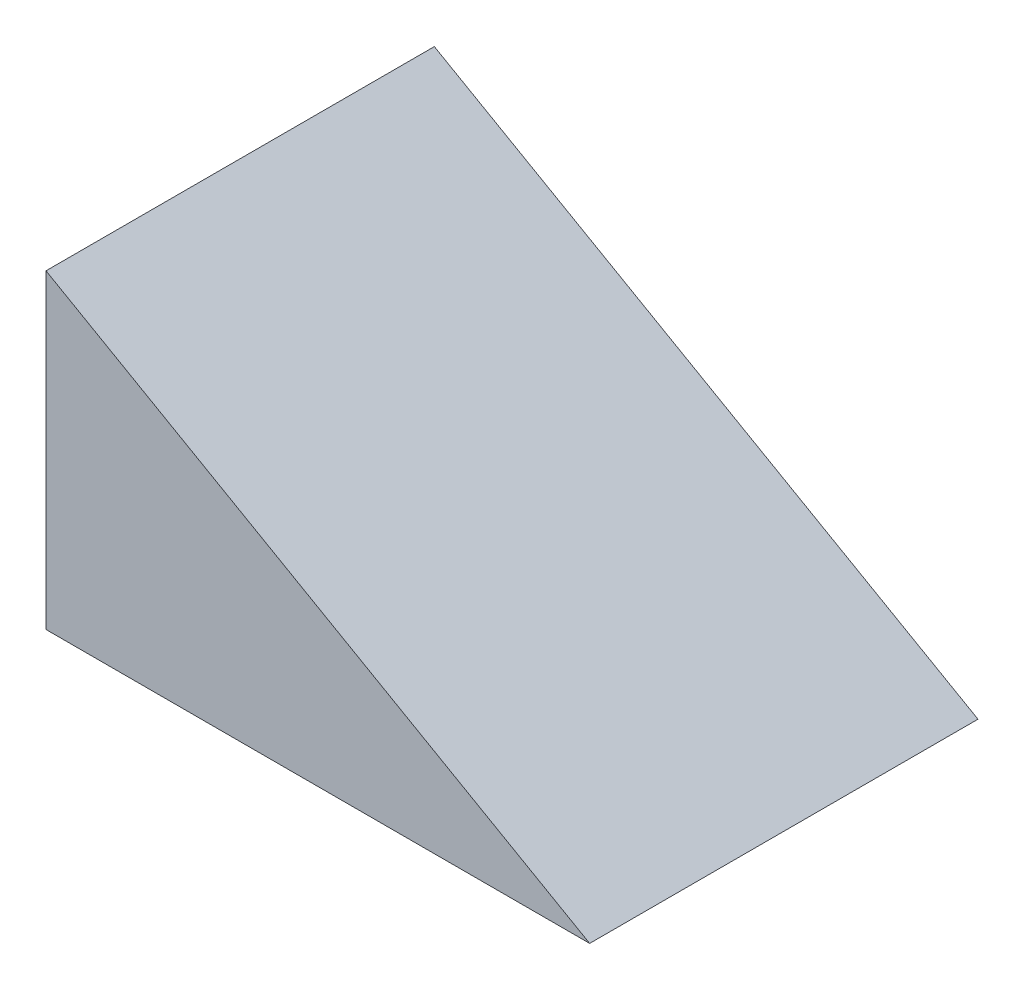
SolidWorks part; units mm, degrees
ref_plane "Front Plane" through (0, 0, 0) normal (0, 0, 1) x (1, 0, 0)
ref_plane "Top Plane" through (0, 0, 0) normal (0, 1, 0) x (1, 0, 0)
ref_plane "Right Plane" through (0, 0, 0) normal (1, 0, 0) x (0, 0, -1)
sketch "Sketch2" plane through (0, 0, 0) normal (0, 0, 1) x (1, 0, 0)
  line L0 (0, 0) -> (70, 0)
  line L1 (70, 0) -> (0, 40)
  line L2 (0, 40) -> (0, 0)
  dimension "D1" = 40
  dimension "D2" = 70
extrude "Boss-Extrude1" add sketch "Sketch2" along normal blind 50
